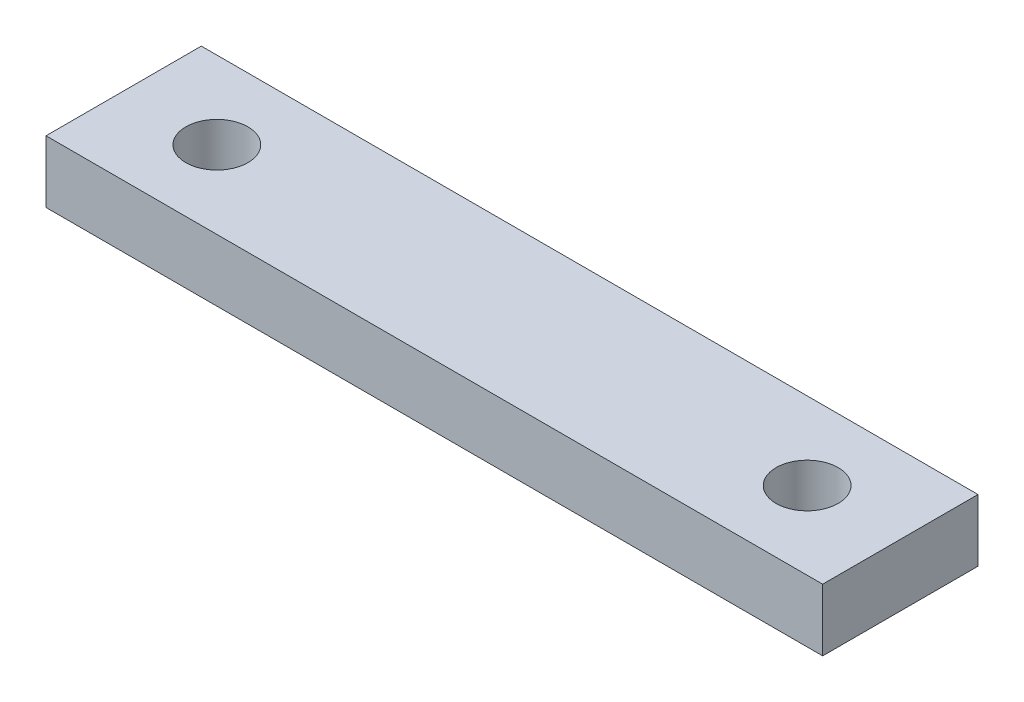
SolidWorks part; units mm, degrees
ref_plane "Front Plane" through (0, 0, 0) normal (0, 0, 1) x (1, 0, 0)
ref_plane "Top Plane" through (0, 0, 0) normal (0, 1, 0) x (1, 0, 0)
ref_plane "Right Plane" through (0, 0, 0) normal (1, 0, 0) x (0, 0, -1)
sketch "Sketch1" plane through (0, 0, 0) normal (0, 1, 0) x (1, 0, 0)
  line L0 (0, 5) -> (0, -5) construction
  line L1 (-25, -5) -> (25, -5)
  line L2 (-25, -5) -> (-25, 5)
  line L3 (-25, 5) -> (25, 5)
  line L4 (25, -5) -> (25, 5)
  line L5 (-25, -5) -> (25, 5) construction
  line L6 (-25, 5) -> (25, -5) construction
  line L7 (19, 5) -> (19, -5) construction
  line L8 (-19, 5) -> (-19, -5) construction
  circle A0 centre (19, 0) radius 2
  circle A1 centre (-19, 0) radius 2
  point P0 (0, 0)
  dimension "D3" = 4
  dimension "D1" = 50
  dimension "D2" = 10
  dimension "D4" = 6
extrude "Boss-Extrude1" add sketch "Sketch1" along normal blind 4
